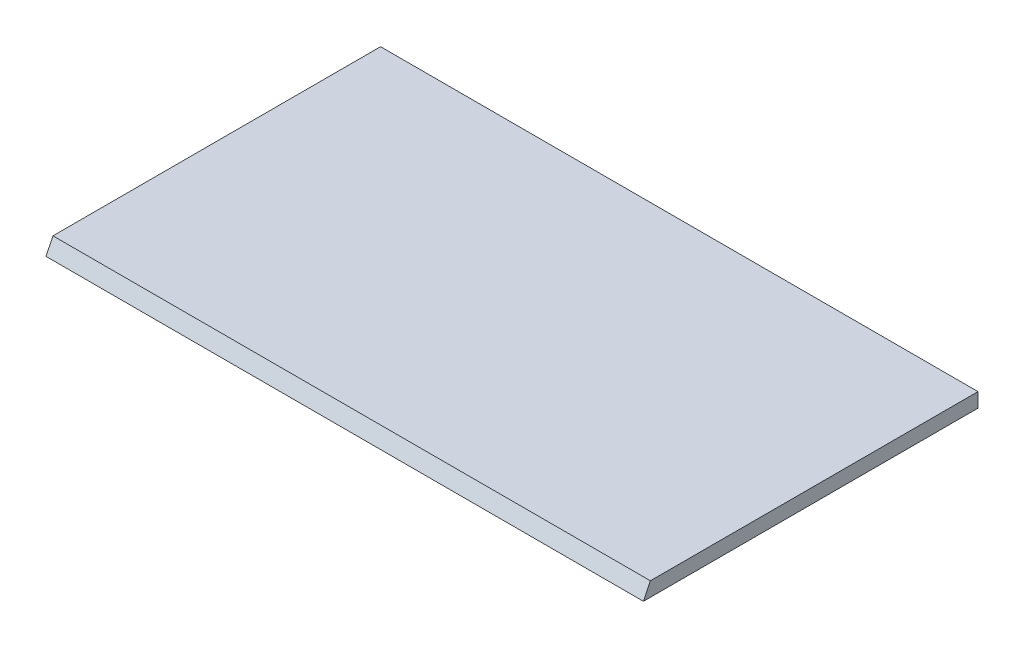
SolidWorks part; units mm, degrees
ref_plane "Plano frontal" through (0, 0, 0) normal (0, 0, 1) x (1, 0, 0)
ref_plane "Plano superior" through (0, 0, 0) normal (0, 1, 0) x (1, 0, 0)
ref_plane "Plano direito" through (0, 0, 0) normal (1, 0, 0) x (0, 0, -1)
sketch "Esboço1" plane through (0, 0, 0) normal (0, 0, 1) x (1, 0, 0)
  line L1 (0, 0) -> (250, 0)
  line L2 (0, 0) -> (0, -6)
  line L3 (0, -6) -> (250, -6)
  line L4 (250, 0) -> (250, -6)
  dimension "D1" = 6
  dimension "D2" = 250
extrude "Ressalto-extrusão1" add sketch "Esboço1" along normal blind 140
sketch "Esboço4" plane through (0, 0, 0) normal (0, 1, 0) x (1, 0, 0)
  line L0 (0, -140) -> (0, -137.1)
  line L1 (0, -140) -> (0, 0) construction
  line L2 (0, -140) -> (0, 0) construction
sketch "Esboço5" plane through (0, 0, 0) normal (-1, 0, 0) x (0, 0, 1)
  line L0 (137.1, 0) -> (140, -6)
  line L1 (140, 0) -> (137.1, 0) construction
  line L2 (140, 0) -> (140, -6) construction
  line L3 (140, -6) -> (140, 0)
  line L4 (140, 0) -> (137.1, 0)
extrude "Corte-extrusão2" cut sketch "Esboço5" against normal through all
